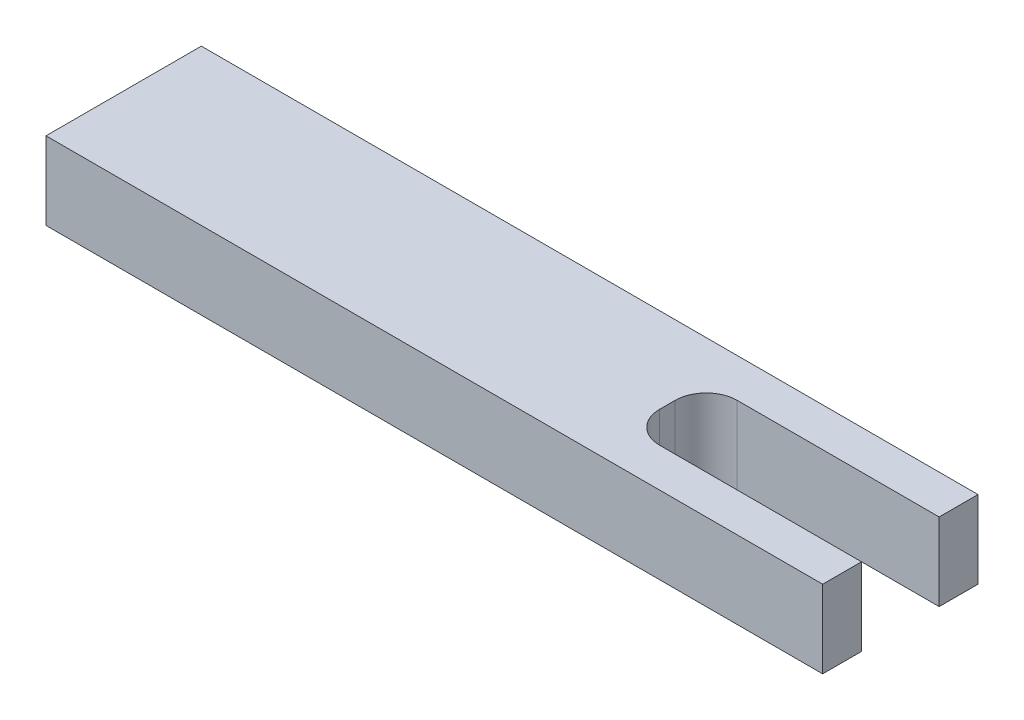
SolidWorks part; units mm, degrees
ref_plane "Alzado" through (0, 0, 0) normal (0, 0, 1) x (1, 0, 0)
ref_plane "Planta" through (0, 0, 0) normal (0, 1, 0) x (1, 0, 0)
ref_plane "Vista lateral" through (0, 0, 0) normal (1, 0, 0) x (0, 0, -1)
sketch "Croquis1" plane through (0, 0, 0) normal (0, 1, 0) x (1, 0, 0)
  line L1 (0, 0) -> (50, 0)
  line L2 (0, 0) -> (0, 10)
  line L3 (0, 10) -> (50, 10)
  line L4 (50, 0) -> (50, 10)
  dimension "D1" = 10
  dimension "D2" = 50
extrude "Saliente-Extruir1" add sketch "Croquis1" along normal mid plane 5
sketch "Croquis2" plane through (0, 2.5, 0) normal (0, 1, 0) x (1, 0, 0)
  line L0 (50, 0) -> (50, 10) construction
  line L1 (50, 7.5) -> (37, 7.5)
  line L2 (50, 7.5) -> (50, 2.5)
  line L3 (50, 2.5) -> (37, 2.5)
  line L4 (35, 5.5) -> (35, 4.5)
  line L5 (0, 5) -> (88.2165, 5) construction
  line L6 (0, 10) -> (0, 0) construction
  arc A0 (37, 2.5) -> (35, 4.5) centre (37, 4.5) cw
  arc A1 (37, 7.5) -> (35, 5.5) centre (37, 5.5) ccw
  point P10 (35, 5)
  point P15 (35, 7.5)
  dimension "D3" = 2
  dimension "D1" = 5
  dimension "D2" = 15
extrude "Cortar-Extruir1" cut sketch "Croquis2" against normal through all
